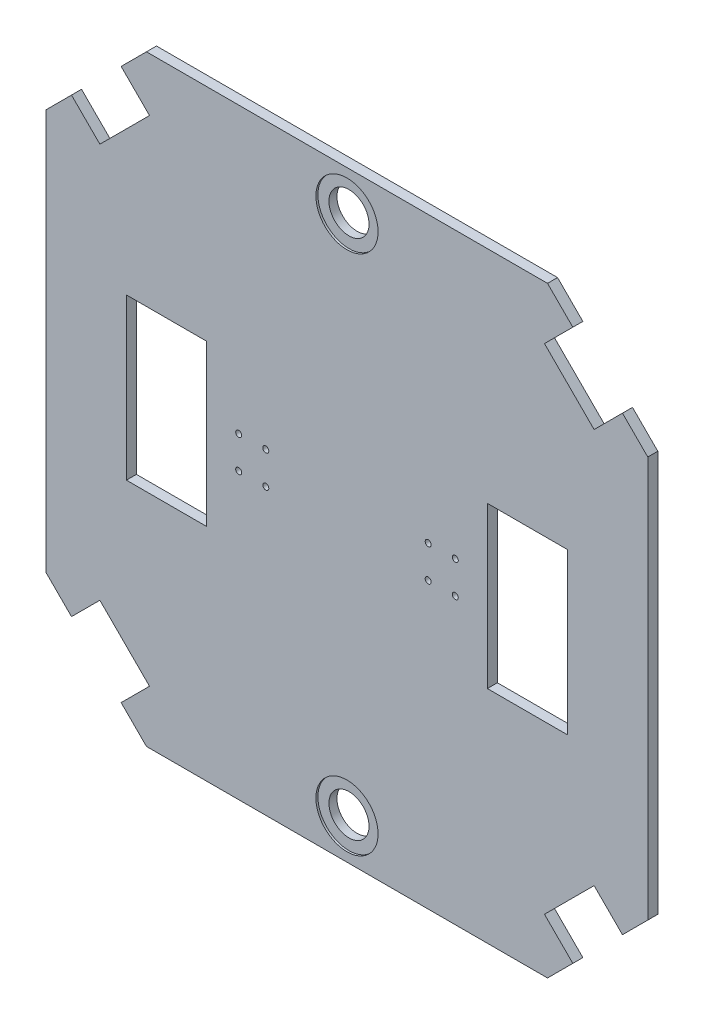
SolidWorks part; units mm, degrees
ref_plane "Plan de face" through (0, 0, 0) normal (0, 0, 1) x (1, 0, 0)
ref_plane "Plan de dessus" through (0, 0, 0) normal (0, 1, 0) x (1, 0, 0)
ref_plane "Plan de droite" through (0, 0, 0) normal (1, 0, 0) x (0, 0, -1)
sketch "Esquisse1" plane through (0, 0, 0) normal (0, 0, 1) x (1, 0, 0)
  line L0 (100, 150) -> (150, 100)
  line L1 (150, -150) -> (-150, -150)
  line L2 (150, -150) -> (150, 150)
  line L3 (150, 150) -> (-150, 150)
  line L4 (-150, -150) -> (-150, 150)
  line L5 (150, -150) -> (-150, 150) construction
  line L6 (150, 150) -> (-150, -150) construction
  line L7 (0, 237.159) -> (0, -197.6632) construction
  line L8 (-230.3021, 0) -> (257.9193, 0) construction
  line L9 (-100, 150) -> (-150, 100)
  line L10 (100, -150) -> (150, -100)
  line L11 (-100, -150) -> (-150, -100)
  line L12 (70, 40) -> (110, 40)
  line L13 (-70, -40) -> (-110, -40)
  line L14 (-70, -40) -> (-70, 40)
  line L15 (-70, 40) -> (-110, 40)
  line L16 (-110, -40) -> (-110, 40)
  line L17 (-70, -40) -> (-110, 40) construction
  line L18 (-70, 40) -> (-110, -40) construction
  line L19 (110, -40) -> (110, 40)
  line L20 (70, -40) -> (110, -40)
  line L21 (70, -40) -> (70, 40)
  line L22 (-137.3744, 112.6256) -> (-123.2322, 98.4835)
  line L23 (-123.2322, 98.4835) -> (-98.4835, 123.2322)
  line L24 (-98.4835, 123.2322) -> (-112.6256, 137.3744)
  line L25 (137.3744, 112.6256) -> (123.2322, 98.4835)
  line L26 (123.2322, 98.4835) -> (98.4835, 123.2322)
  line L27 (98.4835, 123.2322) -> (112.6256, 137.3744)
  line L28 (-137.3744, -112.6256) -> (-123.2322, -98.4835)
  line L29 (-123.2322, -98.4835) -> (-98.4835, -123.2322)
  line L30 (-98.4835, -123.2322) -> (-112.6256, -137.3744)
  line L31 (137.3744, -112.6256) -> (123.2322, -98.4835)
  line L32 (98.4835, -123.2322) -> (112.6256, -137.3744)
  line L33 (123.2322, -98.4835) -> (98.4835, -123.2322)
  circle A0 centre (0, 130) radius 10
  circle A1 centre (0, -130) radius 10
  point P0 (0, 0)
  point P18 (-90, 0)
  point P31 (-110.8579, 110.8579)
  dimension "D10" = 20
  dimension "D1" = 300
  dimension "D2" = 300
  dimension "D3" = 45
  dimension "D4" = 50
  dimension "D5" = 90
  dimension "D6" = 40
  dimension "D7" = 80
  dimension "D8" = 35
  dimension "D9" = 20
  dimension "D11" = 20
extrude "Boss.-Extru.1" add sketch "Esquisse1" along normal blind 5 contours L33 L31 L10 L2 L0 L25 L26 L27 L3 L9 L24 L23 L22 L4 L11 L28 L29 L30 L1 L32 L13 L16 L15 L14 L20 L21 L12 L19
sketch "Esquisse2" plane through (0, 0, 5) normal (0, 0, 1) x (1, 0, 0)
  line L0 (-224.127, 0) -> (220.6881, 0) construction
  circle A0 centre (0, 130) radius 15.5
  circle A1 centre (0, -130) radius 15.5
  dimension "D1" = 31
extrude "Enlèv. mat.-Extru.1" cut sketch "Esquisse2" against normal blind 1
sketch "Esquisse3" plane through (0, 0, 0) normal (0, 0, -1) x (-1, 0, 0)
  line L0 (-184.4245, 0) -> (96.1145, 0) construction
  line L1 (-70, -40) -> (-70, 40) construction
  line L2 (70, -40) -> (70, 40) construction
  circle A8 centre (-40.5, 8.0429) radius 1.5
  circle A9 centre (-40.5, -8.0429) radius 1.5
  circle A10 centre (-54, 8.0429) radius 1.5
  circle A11 centre (-54, -8.0429) radius 1.5
  circle A12 centre (40.5, -8.0429) radius 1.5
  circle A13 centre (54, -8.0429) radius 1.5
  circle A14 centre (54, 8.0429) radius 1.5
  circle A15 centre (40.5, 8.0429) radius 1.5
  point P9 (0, 0)
  point P11 (0, 0)
  point P13 (0, 0)
  point P15 (0, 0)
  point P43 (0, 0)
  point P44 (0, 0)
  point P45 (0, 0)
  point P46 (0, 0)
  point P47 (0, 0)
  point P52 (54.0582, 0)
  dimension "D2" = 3
  dimension "D5" = 3
  dimension "D6" = 3
  dimension "D7" = 3
  dimension "D9" = 3
  dimension "D12" = 3
  dimension "D13" = 3
  dimension "D14" = 3
  dimension "D1" = 8.0429
  dimension "D3" = 16
  dimension "D4" = 13.5
  dimension "D8" = 8.0429
  dimension "D10" = 8.0429
  dimension "D11" = 16
  dimension "D15" = 13.5
extrude "Enlèv. mat.-Extru.2" cut sketch "Esquisse3" against normal through all
